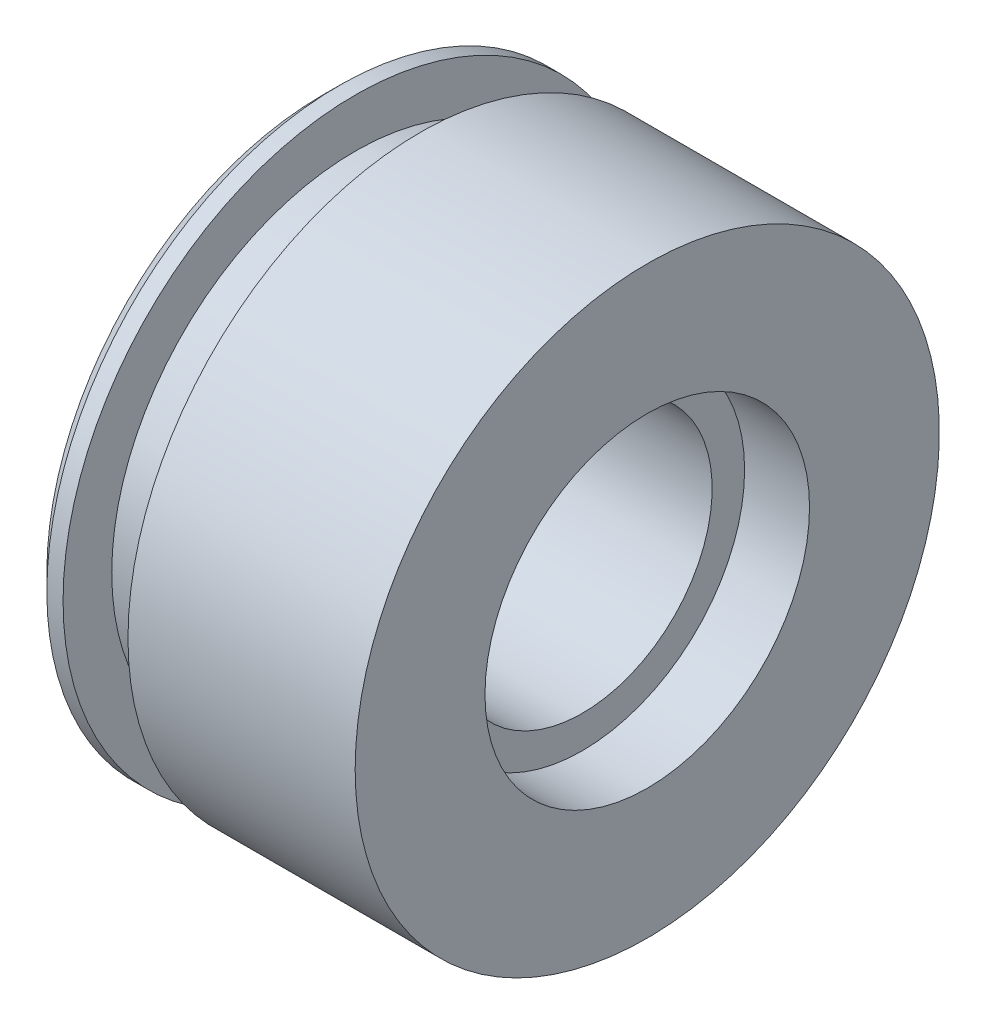
SolidWorks part; units mm, degrees
ref_plane "Alzado" through (0, 0, 0) normal (0, 0, 1) x (1, 0, 0)
ref_plane "Planta" through (0, 0, 0) normal (0, 1, 0) x (1, 0, 0)
ref_plane "Vista lateral" through (0, 0, 0) normal (1, 0, 0) x (0, 0, -1)
sketch "Croquis1" plane through (0, 0, 0) normal (0, 1, 0) x (1, 0, 0)
  line L0 (0, 0) -> (0, 4) construction
  line L1 (0, 4) -> (8, 4)
  line L2 (10, 5) -> (10, 9)
  line L3 (10, 9) -> (3, 9)
  line L4 (3, 9) -> (3, 7.5)
  line L5 (3, 7.5) -> (1, 7.5)
  line L6 (1, 7.5) -> (1, 9)
  line L7 (1, 9) -> (0.5, 9)
  line L8 (0, 8.5) -> (0, 4)
  line L9 (8, 4) -> (8, 5)
  line L10 (8, 5) -> (10, 5)
  line L11 (0.5, 9) -> (0, 8.5)
  line L12 (0, 0) -> (8.775, 0) construction
  point P8 (0, 9)
  dimension "D1" = 4
  dimension "D2" = 1
  dimension "D3" = 4
  dimension "2" = 2
  dimension "D4" = 2
  dimension "D5" = 1
  dimension "D6" = 10
  dimension "D7" = 1.5
  dimension "D9" = 4.5
  dimension "D10" = 1.5
  dimension "D11" = 7.5
revolve "Revolución2" add sketch "Croquis1" angle 360 about L12
